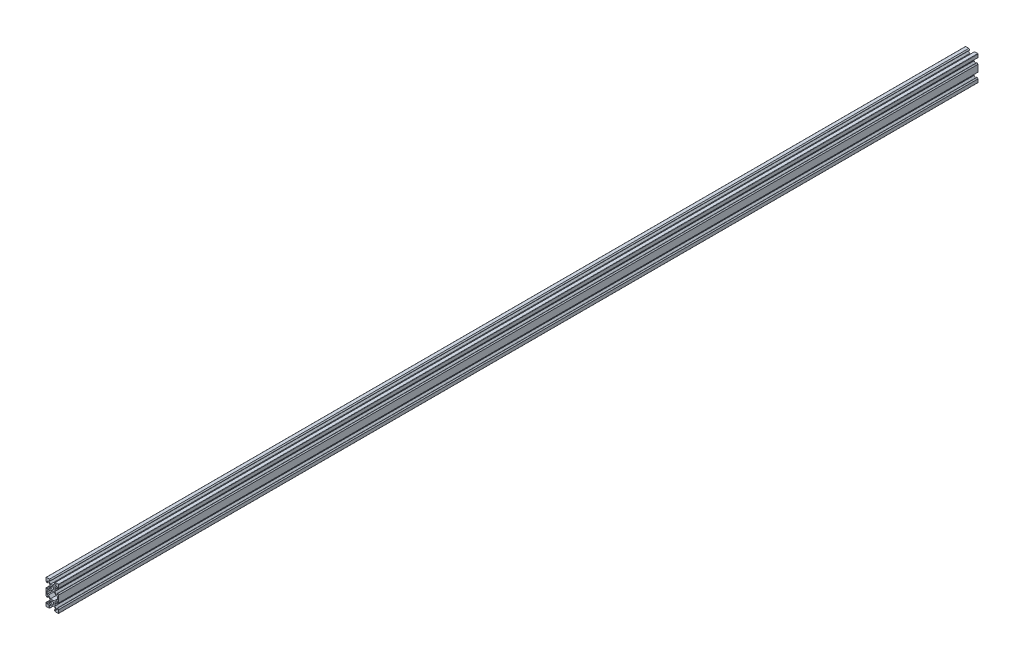
SolidWorks part; units mm, degrees
material "6061-T6 (SS)"
ref_plane "Front Plane" through (0, 0, 0) normal (0, 0, 1) x (1, 0, 0)
ref_plane "Top Plane" through (0, 0, 0) normal (0, 1, 0) x (1, 0, 0)
ref_plane "Right Plane" through (0, 0, 0) normal (1, 0, 0) x (0, 0, -1)
sketch "Sketch1" plane through (0, 0, 0) normal (0, 0, 1) x (1, 0, 0)
  line L0 (0, 0) -> (10, 0) construction
  line L1 (9.5, -20) -> (-9.5, -20)
  line L2 (10, -19.5) -> (10, 19.5)
  line L3 (9.5, 20) -> (-9.5, 20)
  line L4 (-10, -19.5) -> (-10, 19.5)
  line L5 (10, -20) -> (-10, 20) construction
  line L6 (10, 20) -> (-10, -20) construction
  circle A0 centre (0, 10) radius 2.1
  circle A1 centre (0, -10) radius 2.1
  arc A2 (-9.5, -20) -> (-10, -19.5) centre (-9.5, -19.5) cw
  arc A3 (9.5, -20) -> (10, -19.5) centre (9.5, -19.5) ccw
  arc A4 (10, 19.5) -> (9.5, 20) centre (9.5, 19.5) ccw
  arc A5 (-9.5, 20) -> (-10, 19.5) centre (-9.5, 19.5) ccw
  point P0 (0, 0)
  line B0 (0, 10) -> (0, 20) construction
  line B1 (0, 13.69) -> (-0.21, 13.9)
  line B2 (-0.21, 13.9) -> (-2.8393, 13.9)
  line B3 (-2.8393, 13.9) -> (-5.5, 16.5607)
  line B4 (-5.5, 16.5607) -> (-5.5, 18.2)
  line B5 (-5.5, 18.2) -> (-3.125, 18.2)
  line B6 (-3.125, 18.2) -> (-3.125, 18.545)
  line B7 (-3.125, 18.545) -> (-4.58, 20)
  line B8 (-4.58, 20) -> (4.58, 20)
  line B9 (0, 10) -> (-5.9132, 15.9132) construction
  line B10 (3.125, 18.545) -> (4.58, 20)
  line B11 (3.125, 18.2) -> (3.125, 18.545)
  line B12 (5.5, 18.2) -> (3.125, 18.2)
  line B13 (5.5, 16.5607) -> (5.5, 18.2)
  line B14 (2.8393, 13.9) -> (5.5, 16.5607)
  line B15 (0.21, 13.9) -> (2.8393, 13.9)
  line B16 (0, 13.69) -> (0.21, 13.9)
  line B17 (0, 10) -> (-10, 10) construction
  line B18 (-3.69, 10) -> (-3.9, 9.79)
  line B19 (-3.9, 9.79) -> (-3.9, 7.1607)
  line B20 (-3.9, 7.1607) -> (-6.5607, 4.5)
  line B21 (-6.5607, 4.5) -> (-8.2, 4.5)
  line B22 (-8.2, 4.5) -> (-8.2, 6.875)
  line B23 (-8.2, 6.875) -> (-8.545, 6.875)
  line B24 (-8.545, 6.875) -> (-10, 5.42)
  line B25 (-10, 5.42) -> (-10, 14.58)
  line B26 (0, 10) -> (-5.9132, 4.0868) construction
  line B27 (-8.545, 13.125) -> (-10, 14.58)
  line B28 (-8.2, 13.125) -> (-8.545, 13.125)
  line B29 (-8.2, 15.5) -> (-8.2, 13.125)
  line B30 (-6.5607, 15.5) -> (-8.2, 15.5)
  line B31 (-3.9, 12.8393) -> (-6.5607, 15.5)
  line B32 (-3.9, 10.21) -> (-3.9, 12.8393)
  line B33 (-3.69, 10) -> (-3.9, 10.21)
  line B34 (0, -10) -> (-10, -10) construction
  line B35 (-3.69, -10) -> (-3.9, -10.21)
  line B36 (-3.9, -10.21) -> (-3.9, -12.8393)
  line B37 (-3.9, -12.8393) -> (-6.5607, -15.5)
  line B38 (-6.5607, -15.5) -> (-8.2, -15.5)
  line B39 (-8.2, -15.5) -> (-8.2, -13.125)
  line B40 (-8.2, -13.125) -> (-8.545, -13.125)
  line B41 (-8.545, -13.125) -> (-10, -14.58)
  line B42 (-10, -14.58) -> (-10, -5.42)
  line B43 (0, -10) -> (-5.9132, -15.9132) construction
  line B44 (-8.545, -6.875) -> (-10, -5.42)
  line B45 (-8.2, -6.875) -> (-8.545, -6.875)
  line B46 (-8.2, -4.5) -> (-8.2, -6.875)
  line B47 (-6.5607, -4.5) -> (-8.2, -4.5)
  line B48 (-3.9, -7.1607) -> (-6.5607, -4.5)
  line B49 (-3.9, -9.79) -> (-3.9, -7.1607)
  line B50 (-3.69, -10) -> (-3.9, -9.79)
  line B51 (0, -10) -> (0, -20) construction
  line B52 (0, -13.69) -> (0.21, -13.9)
  line B53 (0.21, -13.9) -> (2.8393, -13.9)
  line B54 (2.8393, -13.9) -> (5.5, -16.5607)
  line B55 (5.5, -16.5607) -> (5.5, -18.2)
  line B56 (5.5, -18.2) -> (3.125, -18.2)
  line B57 (3.125, -18.2) -> (3.125, -18.545)
  line B58 (3.125, -18.545) -> (4.58, -20)
  line B59 (4.58, -20) -> (-4.58, -20)
  line B60 (0, -10) -> (5.9132, -15.9132) construction
  line B61 (-3.125, -18.545) -> (-4.58, -20)
  line B62 (-3.125, -18.2) -> (-3.125, -18.545)
  line B63 (-5.5, -18.2) -> (-3.125, -18.2)
  line B64 (-5.5, -16.5607) -> (-5.5, -18.2)
  line B65 (-2.8393, -13.9) -> (-5.5, -16.5607)
  line B66 (-0.21, -13.9) -> (-2.8393, -13.9)
  line B67 (0, -13.69) -> (-0.21, -13.9)
  line B68 (0, -10) -> (10, -10) construction
  line B69 (3.69, -10) -> (3.9, -9.79)
  line B70 (3.9, -9.79) -> (3.9, -7.1607)
  line B71 (3.9, -7.1607) -> (6.5607, -4.5)
  line B72 (6.5607, -4.5) -> (8.2, -4.5)
  line B73 (8.2, -4.5) -> (8.2, -6.875)
  line B74 (8.2, -6.875) -> (8.545, -6.875)
  line B75 (8.545, -6.875) -> (10, -5.42)
  line B76 (10, -5.42) -> (10, -14.58)
  line B77 (0, -10) -> (5.9132, -4.0868) construction
  line B78 (8.545, -13.125) -> (10, -14.58)
  line B79 (8.2, -13.125) -> (8.545, -13.125)
  line B80 (8.2, -15.5) -> (8.2, -13.125)
  line B81 (6.5607, -15.5) -> (8.2, -15.5)
  line B82 (3.9, -12.8393) -> (6.5607, -15.5)
  line B83 (3.9, -10.21) -> (3.9, -12.8393)
  line B84 (3.69, -10) -> (3.9, -10.21)
  line B85 (0, 10) -> (10, 10) construction
  line B86 (3.69, 10) -> (3.9, 10.21)
  line B87 (3.9, 10.21) -> (3.9, 12.8393)
  line B88 (3.9, 12.8393) -> (6.5607, 15.5)
  line B89 (6.5607, 15.5) -> (8.2, 15.5)
  line B90 (8.2, 15.5) -> (8.2, 13.125)
  line B91 (8.2, 13.125) -> (8.545, 13.125)
  line B92 (8.545, 13.125) -> (10, 14.58)
  line B93 (10, 14.58) -> (10, 5.42)
  line B94 (0, 10) -> (5.9132, 15.9132) construction
  line B95 (8.545, 6.875) -> (10, 5.42)
  line B96 (8.2, 6.875) -> (8.545, 6.875)
  line B97 (8.2, 4.5) -> (8.2, 6.875)
  line B98 (6.5607, 4.5) -> (8.2, 4.5)
  line B99 (3.9, 7.1607) -> (6.5607, 4.5)
  line B100 (3.9, 9.79) -> (3.9, 7.1607)
  line B101 (3.69, 10) -> (3.9, 9.79)
  line B102 (-8.2, -2.7) -> (-8.2, 2.7)
  line B103 (-8.2, 2.7) -> (-6.2393, 2.7)
  line B104 (-6.2393, 2.7) -> (-2.8393, 6.1)
  line B105 (-2.8393, 6.1) -> (2.8393, 6.1)
  line B106 (0, 6.1) -> (0, 0) construction
  line B107 (0, 0) -> (-8.2, 0) construction
  line B108 (6.2393, 2.7) -> (2.8393, 6.1)
  line B109 (8.2, 2.7) -> (6.2393, 2.7)
  line B110 (8.2, -2.7) -> (8.2, 2.7)
  line B111 (8.2, -2.7) -> (6.2393, -2.7)
  line B112 (6.2393, -2.7) -> (2.8393, -6.1)
  line B113 (-2.8393, -6.1) -> (2.8393, -6.1)
  line B114 (-6.2393, -2.7) -> (-2.8393, -6.1)
  line B115 (-8.2, -2.7) -> (-6.2393, -2.7)
  line B116 (0, 6.1) -> (0, 10) construction
  line B117 (0, 10) -> (-5.0927, 4.9073) construction
  dimension "D4" = 4.2
  dimension "D5" = 0.5
  dimension "D1" = 20
  dimension "D2" = 40
  dimension "D3" = 20
sketch_block_instance "V Slot 1-4"
sketch_block "V Slot 1" parameters "D1"=10, "D2"=11, "D3"=4.3, "D4"=1.8, "D5"=0.21, "D6"=45, "D7"=9.16, "D8"=1.5, "D9"=6.25
sketch_block_instance "V Slot 1-5"
sketch_block_instance "V Slot 1-6"
sketch_block_instance "V Slot 1-7"
sketch_block_instance "V Slot 1-8"
sketch_block_instance "V Slot 1-9"
sketch_block_instance "Center Cutout 1-1"
sketch_block "Center Cutout 1" parameters "D1"=5.4, "D2"=12.2, "D3"=8.2, "D4"=45, "D5"=10, "D6"=1.5
extrude "Boss-Extrude1" add sketch "Sketch1" along normal blind 1455 contours B101 B86 B87 B88 B89 B90 B91 B92 L2 A4 L3 B10 B11 B12 B13 B14 B15 B16 B1 B2 B3 B4 B5 B6 B7 A5 L4 B27 B28 B29 B30 B31 B32 B33 B18 B19 B20 B21 B22 B23 B24 B44 B45 B46 B47 B48 B49 B50 B35
